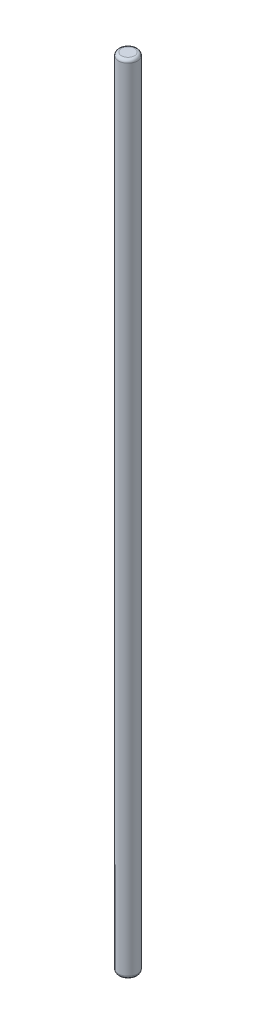
SolidWorks part; units mm, degrees
ref_plane "Front Plane" through (0, 0, 0) normal (0, 0, 1) x (1, 0, 0)
ref_plane "Top Plane" through (0, 0, 0) normal (0, 1, 0) x (1, 0, 0)
ref_plane "Right Plane" through (0, 0, 0) normal (1, 0, 0) x (0, 0, -1)
sketch "Sketch1" plane through (0, 0, 0) normal (0, 1, 0) x (1, 0, 0)
  circle A0 centre (0, 0) radius 0.95
  dimension "D1" = 1.9
extrude "Boss-Extrude1" add sketch "Sketch1" along normal blind 80
fillet "Fillet1" radius 0.3 2 edges at (0, 0, 0.95) (0, 80, 0.95)
